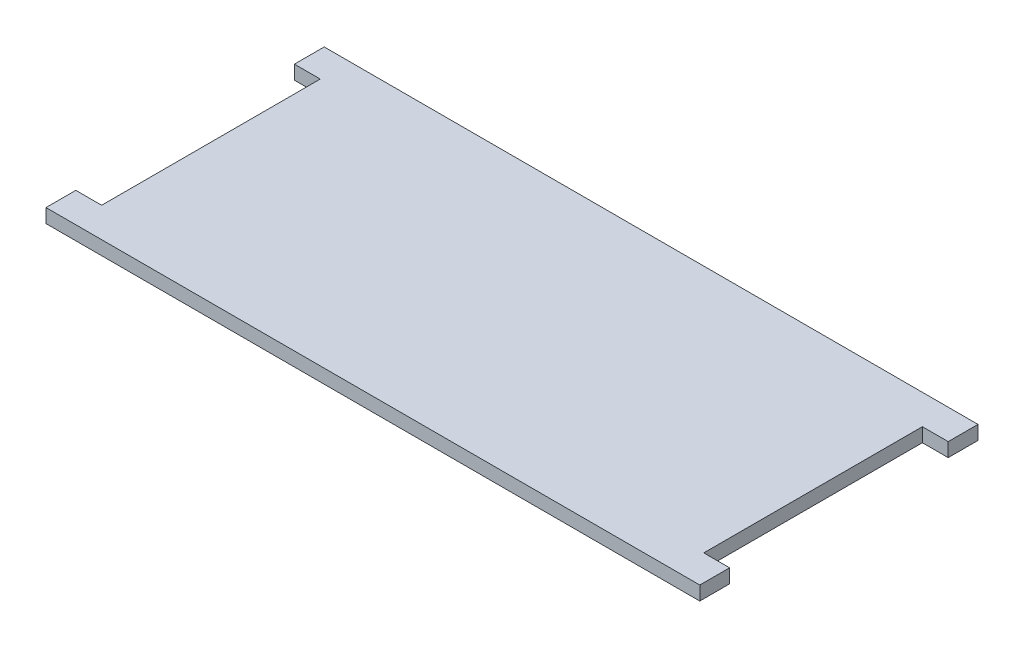
SolidWorks part; units mm, degrees
ref_plane "Plan de face" through (0, 0, 0) normal (0, 0, 1) x (1, 0, 0)
ref_plane "Plan de dessus" through (0, 0, 0) normal (0, 1, 0) x (1, 0, 0)
ref_plane "Plan de droite" through (0, 0, 0) normal (1, 0, 0) x (0, 0, -1)
sketch "Esquisse1" plane through (0, 0, 0) normal (1, 0, 0) x (0, 0, -1)
  line L1 (-70, -3.5) -> (70, -3.5)
  line L2 (-70, -3.5) -> (-70, 3.5)
  line L3 (-70, 3.5) -> (70, 3.5)
  line L4 (70, -3.5) -> (70, 3.5)
extrude "Boss.-Extru.1" add sketch "Esquisse1" along normal blind 329
sketch "Esquisse2" plane through (0, 3.5, 0) normal (0, 1, 0) x (1, 0, 0)
  line L1 (13, 122.09) -> (13, -122.09)
  line L4 (316, 122.09) -> (316, -122.09)
  line L5 (13, 122.09) -> (316, 122.09)
  line L6 (13, -122.09) -> (316, -122.09)
  point P6 (13, 0)
extrude "Boss.-Extru.2" add sketch "Esquisse2" against normal up to vertex (7 mm away)
sketch "Esquisse3" plane through (0, 3.5, 0) normal (0, 1, 0) x (1, 0, 0)
  line L1 (0, 70) -> (0, -70) construction
  line L2 (-45.8735, 0) -> (369.228, 0) construction
  line L3 (164.5, 122.09) -> (164.5, -142.8268) construction
  line L4 (316, 122.09) -> (13, 122.09) construction
  line L6 (0, -55) -> (13, -55)
  line L9 (0, 55) -> (13, 55)
  line L12 (329, 55) -> (316, 55)
  line L13 (329, -55) -> (316, -55)
  line L16 (13, 55) -> (13, -55)
  line L18 (316, 55) -> (316, -55)
  line L19 (0, 55) -> (0, -55)
  line L20 (329, 55) -> (329, -55)
extrude "Enlèv. mat.-Extru.1" cut sketch "Esquisse3" against normal blind 96
sketch "Esquisse4" plane through (0, 3.5, 0) normal (0, 1, 0) x (1, 0, 0)
  line L0 (13, 70) -> (316, 70)
  line L1 (316, 70) -> (318.7653, 132.4471)
  line L2 (318.7653, 132.4471) -> (0, 132.4471)
  line L3 (0, 132.4471) -> (13, 70)
  line L4 (13, -70) -> (316, -70)
  line L5 (316, -70) -> (321.2576, -130.6669)
  line L6 (321.2576, -130.6669) -> (0, -142.4163)
  line L7 (0, -142.4163) -> (13, -70)
extrude "Enlèv. mat.-Extru.2" cut sketch "Esquisse4" against normal blind 96
